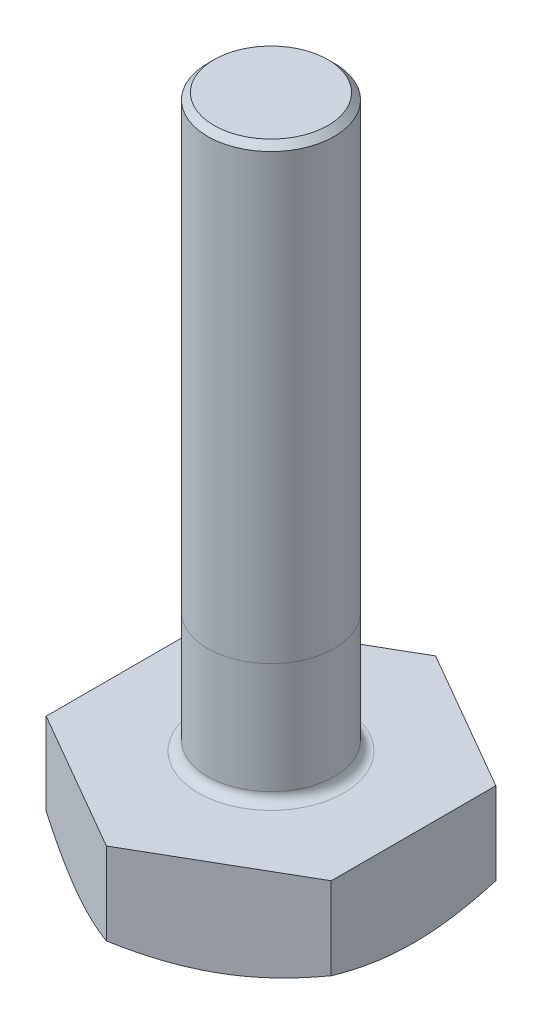
SolidWorks part; units mm, degrees
ref_plane "Alzado" through (0, 0, 0) normal (0, 0, 1) x (1, 0, 0)
ref_plane "Planta" through (0, 0, 0) normal (0, 1, 0) x (1, 0, 0)
ref_plane "Vista lateral" through (0, 0, 0) normal (1, 0, 0) x (0, 0, -1)
sketch "Croquis2" plane through (0, 0, 0) normal (0, 1, 0) x (1, 0, 0)
  line L1 (0, -2.5981) -> (2.25, -1.299)
  line L2 (2.25, -1.299) -> (2.25, 1.299)
  line L3 (2.25, 1.299) -> (0, 2.5981)
  line L4 (0, 2.5981) -> (-2.25, 1.299)
  line L5 (-2.25, 1.299) -> (-2.25, -1.299)
  line L6 (-2.25, -1.299) -> (0, -2.5981)
  circle A0 centre (0, 0) radius 2.25 construction
  circle A1 centre (0, 0) radius 1 construction
  dimension "D1" = 2
  dimension "D2" = 4.5
extrude "Saliente-Extruir1" add sketch "Croquis2" along normal blind 1.5
sketch "Croquis3" plane through (0, 0, 0) normal (0, 1, 0) x (1, 0, 0)
  circle A0 centre (0, 0) radius 2.25 construction
  circle A1 centre (0, 0) radius 2.25
extrude "Cortar-Extruir6" cut sketch "Croquis3" along normal blind 1.5 draft 60 flip side to cut
sketch "Croquis4" plane through (0, 1.5, 0) normal (0, 1, 0) x (1, 0, 0)
  circle A0 centre (0, 0) radius 1 construction
  circle A1 centre (0, 0) radius 1
extrude "Saliente-Extruir2" add sketch "Croquis4" along normal blind 9
chamfer "Chaflán1" distance 0.1 angle 45 1 edges at (0, 10.5, 1)
fillet "Redondeo1" radius 0.15 1 edges at (0, 1.5, 1)
sketch "Croquis6" plane through (0, 0, 0) normal (1, 0, 0) x (0, 0, -1)
  line L0 (-2.3552, 3.4) -> (2.3552, 3.4)
  line L1 (-1, 10.4) -> (1, 10.4) construction
  point P2 (0, 3.4)
  dimension "D1" = 7
split line "Línea de partición1"
